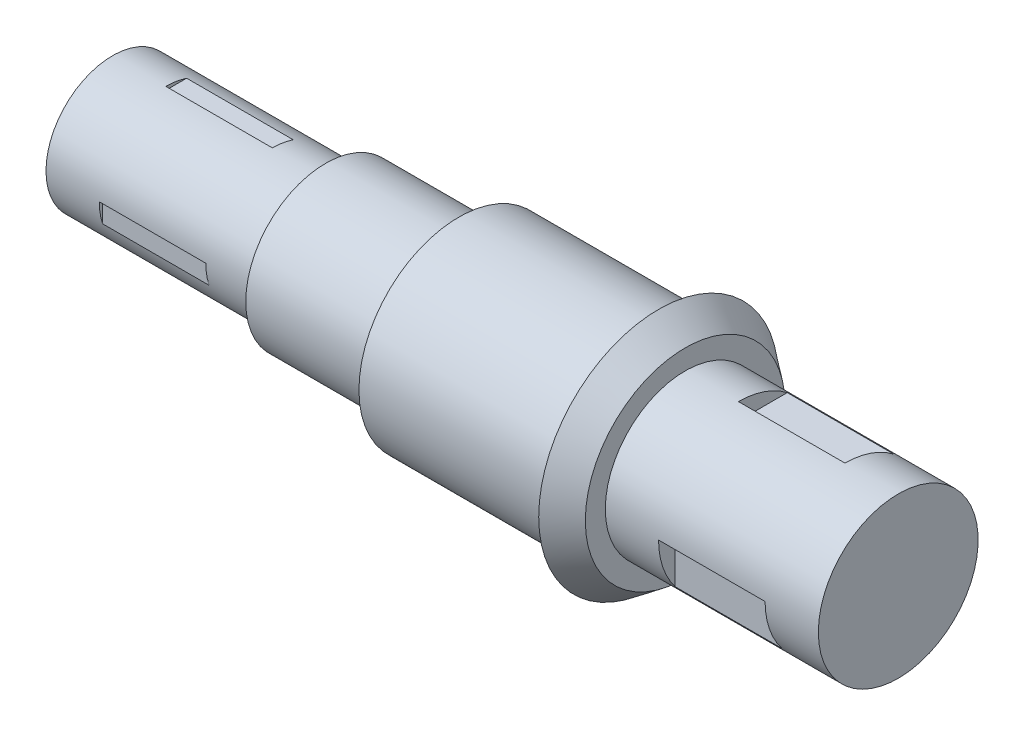
SolidWorks part; units mm, degrees
ref_plane "Front Plane" through (0, 0, 0) normal (0, 0, 1) x (1, 0, 0)
ref_plane "Top Plane" through (0, 0, 0) normal (0, 1, 0) x (1, 0, 0)
ref_plane "Right Plane" through (0, 0, 0) normal (1, 0, 0) x (0, 0, -1)
sketch "Sketch1" plane through (0, 0, 0) normal (0, 0, 1) x (1, 0, 0)
  line L0 (0, 0) -> (59, 0) construction
  line L1 (0, 0) -> (0, 5)
  line L2 (0, 5) -> (16, 5)
  line L3 (16, 5) -> (16, 6)
  line L4 (16, 6) -> (26, 6)
  line L5 (26, 6) -> (26, 7.5)
  line L6 (26, 7.5) -> (41, 7.5)
  line L7 (41, 7.5) -> (41, 9)
  line L8 (41, 9) -> (43, 7.5)
  line L9 (43, 7.5) -> (43, 6)
  line L10 (43, 6) -> (59, 6)
  line L11 (59, 6) -> (59, 0)
  line L12 (59, 0) -> (0, 0)
revolve "Revolve-Shaft" add sketch "Sketch1" angle 360 about L0
sketch "Sketch2" plane through (0, 0, 0) normal (0, 1, 0) x (1, 0, 0)
  line L1 (4, 4.75) -> (12, 4.75)
  line L2 (4, 4.75) -> (4, 15)
  line L3 (4, 15) -> (12, 15)
  line L4 (12, 4.75) -> (12, 15)
  line L5 (4, -4.75) -> (12, -4.75)
  line L6 (4, -4.75) -> (4, -15)
  line L7 (4, -15) -> (12, -15)
  line L8 (12, -4.75) -> (12, -15)
extrude "Cut-Flats Top-Bot Left" cut sketch "Sketch2" against normal blind 30
sketch "Sketch3" plane through (0, 0, 0) normal (0, 0, 1) x (1, 0, 0)
  line L1 (4, 4.75) -> (12, 4.75)
  line L2 (4, 4.75) -> (4, 15)
  line L3 (4, 15) -> (12, 15)
  line L4 (12, 4.75) -> (12, 15)
  line L5 (4, -4.75) -> (12, -4.75)
  line L6 (4, -4.75) -> (4, -15)
  line L7 (4, -15) -> (12, -15)
  line L8 (12, -4.75) -> (12, -15)
extrude "Cut-Flats Sides Left" cut sketch "Sketch3" against normal blind 30
sketch "Sketch4" plane through (0, 0, 0) normal (0, 1, 0) x (1, 0, 0)
  line L1 (47, 4.75) -> (55, 4.75)
  line L2 (47, 4.75) -> (47, 15)
  line L3 (47, 15) -> (55, 15)
  line L4 (55, 4.75) -> (55, 15)
  line L5 (47, -4.75) -> (55, -4.75)
  line L6 (47, -4.75) -> (47, -15)
  line L7 (47, -15) -> (55, -15)
  line L8 (55, -4.75) -> (55, -15)
extrude "Cut-Flats Top-Bot Right" cut sketch "Sketch4" against normal blind 30
sketch "Sketch5" plane through (0, 0, 0) normal (0, 0, 1) x (1, 0, 0)
  line L1 (47, 4.75) -> (55, 4.75)
  line L2 (47, 4.75) -> (47, 15)
  line L3 (47, 15) -> (55, 15)
  line L4 (55, 4.75) -> (55, 15)
  line L5 (47, -4.75) -> (55, -4.75)
  line L6 (47, -4.75) -> (47, -15)
  line L7 (47, -15) -> (55, -15)
  line L8 (55, -4.75) -> (55, -15)
extrude "Cut-Flats Sides Right" cut sketch "Sketch5" against normal blind 30
